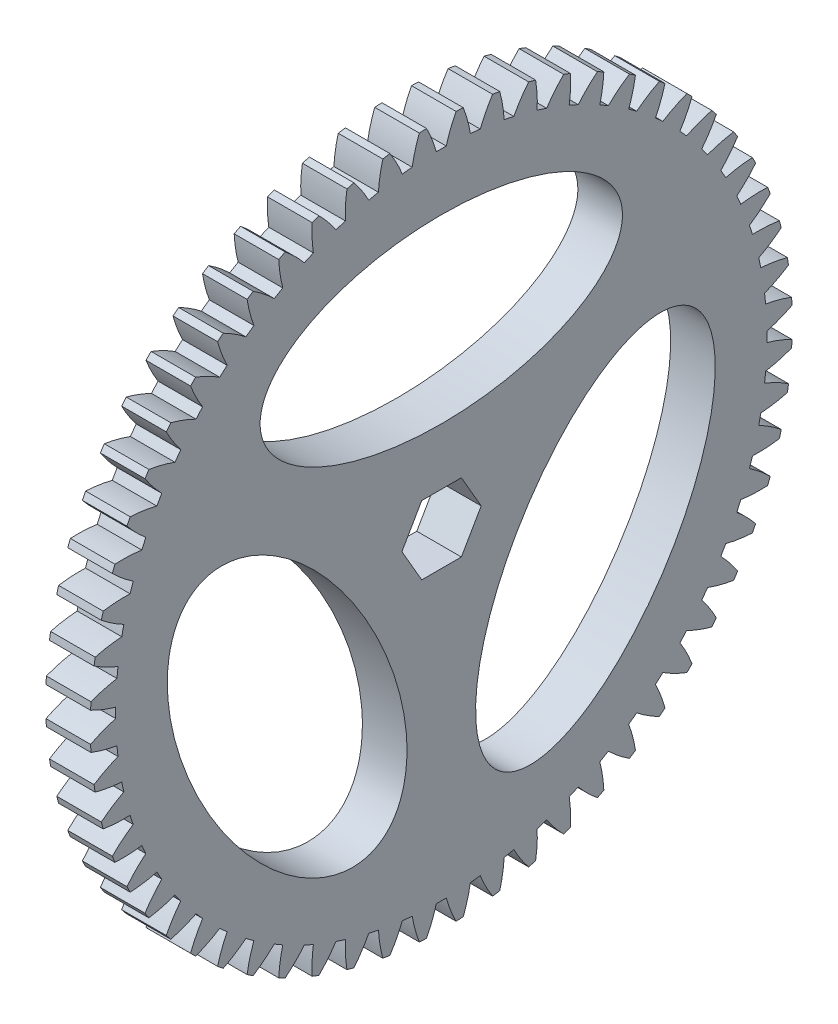
SolidWorks part; units mm, degrees
ref_plane "Plane1" through (0, 0, 0) normal (0, 0, 1) x (1, 0, 0)
ref_plane "Plane2" through (0, 0, 0) normal (0, 1, 0) x (1, 0, 0)
ref_plane "Plane3" through (0, 0, 0) normal (1, 0, 0) x (0, 0, -1)
sketch "HoldingSke" plane through (0, 0, 0) normal (0, 1, 0) x (1, 0, 0)
  line L0 (0, 0) -> (254, -439.9409)
  line L1 (-15, 0) -> (100, 0) construction
  line L2 (0, 0) -> (-2.1039, 2.3779)
  line L3 (0, 0) -> (-11.863, 4.5341)
  line L4 (0, 0) -> (4.318, 7.479)
  line L5 (0, 0) -> (-47.5972, -17.7524)
  line L6 (0, 0) -> (-4.1448, -2.7965)
  line L7 (-2.1039, 2.3779) -> (8.8308, 51.9871)
  line L8 (-76.2, 54.61) -> (-75.184, 54.61)
  line L9 (-71.009, 38.7566) -> (-53.1078, 45.2721)
  line L10 (-76.2, 71.12) -> (104.1128, 71.12)
  line L11 (0, 0) -> (-5, 0)
  line L12 (-76.2, 101.6) -> (-76.1492, 101.6)
  line L13 (24.9733, 27.94) -> (52.9518, 28.4284)
  line L14 (24.9733, 27.94) -> (25.0241, 27.9398)
  line L15 (24.9733, 27.94) -> (100.4021, 29.52)
  circle A0 centre (0, 0) radius 0.3969
  circle A1 centre (0, 0) radius 36.5252
  circle A2 centre (0, 0) radius 38.1
  circle A3 centre (0, 0) radius 0.3969
  dimension "MHD" = 73.0504
  dimension "Hub_dia" = 76.2
  dimension "Bore" = 0.7937
  dimension "MBD" = 0.7937
  dimension "Num_teeth" = 60
  dimension "Pitch" = 508
  dimension "Overall_len" = 50.8
  dimension "Show_teeth" = 60
  dimension "Thickness" = 5
  dimension "OAL" = 50.8001
  dimension "T_dim" = 1.016
  dimension "Ap" = 20
  dimension "H" = 19.05
  dimension "Pitch_radius" = 180.3128
  dimension "Width" = 5
  dimension "Backlash" = 0.0508
  dimension "Addendum_fac" = 1
  dimension "Dedendum_fac" = 1.2
  dimension "Clearance_fac" = 0.2
  dimension "Dedendum_add" = 0.0508
sketch "BasProSke" plane through (0, 0, 0) normal (0, 1, 0) x (1, 0, 0)
  line L0 (-10, 0) -> (60, 0) construction
  line L1 (0, 0) -> (0, 39.37)
  line L2 (0, 0) -> (5, 0)
  line L3 (5, 0) -> (5, 39.37)
  line L4 (5, 39.37) -> (0, 39.37)
  dimension "Thickness" = 5
  dimension "Diameter" = 78.74
revolve "Base-Revolve" add sketch "BasProSke" angle 360 about L0
sketch "TooCutSke" plane through (0, 0, 0) normal (1, 0, 0) x (0, 0, -1)
  line L1 (0, 0) -> (0, 107) construction
  line L2 (0, 0) -> (-1.0862, 38.0845) construction
  line L3 (0, 0) -> (-3.9869, 76.0739) construction
  line L4 (-1.0862, 38.0845) -> (-1.9934, 38.037) construction
  arc A0 (0.5545, 36.521) -> (-0.5545, 36.521) centre (0, 0) ccw
  arc A1 (1.6683, 39.3601) -> (-1.6683, 39.3601) centre (0, 0) ccw
  circle A2 centre (0, 0) radius 38.1 construction
  circle A3 centre (0, 0) radius 35.8023 construction
  arc A4 (-0.5545, 36.521) -> (-1.6683, 39.3601) centre (-15.2274, 32.4026) ccw
  arc A5 (1.6683, 39.3601) -> (0.5545, 36.521) centre (15.2274, 32.4026) ccw
  dimension "Root_dia" = 73.0504
  dimension "Overcut_dia" = 78.7908
  dimension "Pitch_dia" = 76.2
  dimension "Base_dia" = 71.6046
  dimension "Flank_rad" = 15.24
  dimension "Half_ang" = 3
  dimension "Half_CT" = 0.9084
extrude "ToothCut" cut sketch "TooCutSke" along normal through all
fillet "Breaks" [suppressed] radius 0.0254
fillet "RootFillets" [suppressed] radius 0.3048
pattern_circular "TeethCuts" count 60 every 6 about axis through (-10, 0, 0) along (1, 0, 0) of "ToothCut", "RootFillets", "Breaks"
sketch "HubNeaOneSke" plane through (0, 0, 0) normal (-1, 0, 0) x (0, 0, 1)
  circle A0 centre (0, 0) radius 36.5252
  dimension "Diameter" = 73.0504
extrude "HubNearOne" [suppressed] add sketch "HubNeaOneSke" along normal blind 45.8001
sketch "HubNeaBotSke" plane through (0, 0, 0) normal (-1, 0, 0) x (0, 0, 1)
  circle A0 centre (0, 0) radius 36.5252
  dimension "Diameter" = 73.0504
extrude "HubNearBoth" [suppressed] add sketch "HubNeaBotSke" along normal blind 22.9
ref_plane "FarPln" through (5, 0, 0) normal (1, 0, 0) x (0, 0, -1)
sketch "HubFarSke" plane through (5, 0, 0) normal (1, 0, 0) x (0, 0, -1)
  circle A0 centre (0, 0) radius 36.5252
  dimension "Diameter" = 73.0504
extrude "HubFar" [suppressed] add sketch "HubFarSke" along normal blind 22.9
sketch "BorSke" plane through (0, 0, 0) normal (1, 0, 0) x (0, 0, -1)
  circle A0 centre (0, 0) radius 0.3969
  dimension "Diameter" = 0.7937
extrude "Bore" cut sketch "BorSke" along normal mid plane 101.6001
sketch "KeySke" plane through (0, 0, 0) normal (1, 0, 0) x (0, 0, -1)
  line L0 (-0.127, 0) -> (-0.127, 0.6191)
  line L1 (-0.127, 0.6191) -> (0.127, 0.6191)
  line L2 (0.127, 0.6191) -> (0.127, 0)
  line L3 (0, 0) -> (0, 34) construction
  line L4 (-0.127, 0) -> (0.127, 0)
  dimension "Offset" = 0.6191
  dimension "Width" = 0.254
extrude "Keyway" [suppressed] cut sketch "KeySke" along normal mid plane 101.6001
pattern_circular "Keyway2" [suppressed] count 2 every 90 about axis through (-10, 0, 0) along (1, 0, 0)
sketch "Sketch1" plane through (5, 0, 0) normal (1, 0, 0) x (0, 0, -1)
  line L1 (2.2518, 3.4537) -> (-2.1932, 3.4537)
  line L2 (-2.1932, 3.4537) -> (-4.4157, -0.3958)
  line L3 (-4.4157, -0.3958) -> (-2.1932, -4.2453)
  line L4 (-2.1932, -4.2453) -> (2.2518, -4.2453)
  line L5 (2.2518, -4.2453) -> (4.4743, -0.3958)
  line L6 (4.4743, -0.3958) -> (2.2518, 3.4537)
  circle A0 centre (0.0293, -0.3958) radius 3.8495 construction
  circle A1 centre (0, 0) radius 0.3969 construction
  dimension "D1" = 8.89
extrude "Cut-Extrude1" cut sketch "Sketch1" against normal through all
sketch "Sketch2" plane through (5, 0, 0) normal (1, 0, 0) x (0, 0, -1)
  line L0 (2.2518, 3.4537) -> (-2.1932, 3.4537) construction
  ellipse E0 centre (0, 19.9637) end of major axis (20.32, 19.9637) minor radius 10.16
  dimension "D1" = 6.35
  dimension "D2" = 20.32
  dimension "D3" = 40.64
extrude "Cut-Extrude2" cut sketch "Sketch2" against normal through all
pattern_circular "CirPattern1" count 3 over 360 about axis through (5, 0, 0) along (-1, 0, 0) of "Cut-Extrude2"
equation "' \"Pitch@HoldingSke\" = 4"
equation "' \"Num_teeth@HoldingSke\" = 12"
equation "' \"Ap@HoldingSke\" =  20"
equation "' \"Ap@HoldingSke\" = 20"
equation "' \"Width@HoldingSke\" = 0.5"
equation "' \"Hub_dia@HoldingSke\"= 1"
equation "' \"Hub_dia@HoldingSke\" = 1"
equation "' \"Overall_len@HoldingSke\" = 1.0"
equation "' \"Bore@HoldingSke\" = 0.75"
equation "' \"T_dim@HoldingSke\" = 0.85"
equation "' \"Width@KeySke\" = 0.25"
equation "' \"Show_teeth@HoldingSke\" = 13"
equation "' \"Backlash@HoldingSke\" = 0.009"
equation "' \"Addendum_fac@HoldingSke\" = 1.0"
equation "' \"Dedendum_fac@HoldingSke\" = 1.25"
equation "' \"Dedendum_add@HoldingSke\" = 0.00005"
equation "' \"Clearance_fac@HoldingSke\" = 0.25"
equation "' \"Pitch@HoldingSke\" = 0.5"
equation "' \"Num_teeth@HoldingSke\" = 23"
equation "' \"Show_teeth@HoldingSke\" = 23"
equation "' \"Backlash@HoldingSke\" = 0.0375"
equation "\"Overcut_dia@TooCutSke\" = (\"Num_teeth@HoldingSke\" + 2 * \"Addendum_fac@HoldingSke\") / \"Pitch@HoldingSke\" + 0.002"
equation "\"Pitch_dia@TooCutSke\" = \"Num_teeth@HoldingSke\" / \"Pitch@HoldingSke\""
equation "\"Base_dia@TooCutSke\" = \"Num_teeth@HoldingSke\" / \"Pitch@HoldingSke\" * cos((\"Ap@HoldingSke\"  * 3.14159265 / 180))"
equation "\"Root_dia@TooCutSke\" = (\"Num_teeth@HoldingSke\" + 2) / \"Pitch@HoldingSke\" - 2 * (\"Addendum_fac@HoldingSke\" + \"Dedendum_fac@HoldingSke\") / \"Pitch@HoldingSke\" - \"Dedendum_add@HoldingSke\" * 2"
equation "\"Half_ang@TooCutSke\" = 180 / \"Num_teeth@HoldingSke\""
equation "\"Half_CT@TooCutSke\" = \"Num_teeth@HoldingSke\" / \"Pitch@HoldingSke\" * sin((3.14159265 / 2 / \"Num_teeth@HoldingSke\")) / 2 - 7 * \"Backlash@HoldingSke\" / 4"
equation "\"Flank_rad@TooCutSke\" = \"Num_teeth@HoldingSke\" / \"Pitch@HoldingSke\" / 5"
equation "\"Radius@RootFillets\" = \"Clearance_fac@HoldingSke\" / \"Pitch@HoldingSke\" + \"Dedendum_add@HoldingSke\""
equation "\"Break_rad@Breaks\" = 0.02 / \"Pitch@HoldingSke\""
equation "\"Thickness@HoldingSke\" = \"Width@HoldingSke\""
equation "\"OAL@HoldingSke\" = \"Thickness@HoldingSke\""
equation "\"MHD@HoldingSke\" = (\"Num_teeth@HoldingSke\" + 2) / \"Pitch@HoldingSke\" - 2 * (\"Addendum_fac@HoldingSke\" + \"Dedendum_fac@HoldingSke\")  / \"Pitch@HoldingSke\" - \"Dedendum_add@HoldingSke\" * 2"
equation "\"MBD@HoldingSke\" = (\"Num_teeth@HoldingSke\" + 2) / \"Pitch@HoldingSke\" - 2 * (\"Addendum_fac@HoldingSke\" + \"Dedendum_fac@HoldingSke\")  / \"Pitch@HoldingSke\" - \"Dedendum_add@HoldingSke\" * 2 - 0.002"
equation "\"MHD@HoldingSke\" = ((sgn( \"MHD@HoldingSke\" - \"Hub_dia@HoldingSke\" )-1)*( \"MHD@HoldingSke\" - \"Hub_dia@HoldingSke\" ))/-2+ \"Hub_dia@HoldingSke\""
equation "\"MBD@HoldingSke\" = ((sgn( \"MBD@HoldingSke\" - \"Bore@HoldingSke\" )-1)*( \"MBD@HoldingSke\" - \"Bore@HoldingSke\" ))/-2+ \"Bore@HoldingSke\""
equation "\"OAL@HoldingSke\" = ((sgn( \"OAL@HoldingSke\" - \"Overall_len@HoldingSke\" )+1)*( \"OAL@HoldingSke\" - \"Overall_len@HoldingSke\" ))/2 + \"Overall_len@HoldingSke\" + 0.000002"
equation "\"Num_teeth@TeethCuts\" = int( \"Show_teeth@HoldingSke\" ) + 1"
equation "\"Num_teeth@TeethCuts\" = ((sgn( \"Num_teeth@TeethCuts\" - \"Num_teeth@HoldingSke\" )-1)*( \"Num_teeth@TeethCuts\" - \"Num_teeth@HoldingSke\" ))/-2+ \"Num_teeth@HoldingSke\""
equation "\"Num_teeth@TeethCuts\" = ((sgn( \"Num_teeth@TeethCuts\" - 2.0)+1)*( \"Num_teeth@TeethCuts\" - 2.0))/2 +2.0"
equation "\"Angle@TeethCuts\" = 360.0 / \"Num_teeth@HoldingSke\""
equation "\"Diameter@BasProSke\" = (\"Num_teeth@HoldingSke\" + 2 * \"Addendum_fac@HoldingSke\") / \"Pitch@HoldingSke\""
equation "\"Thickness@BasProSke\"  = \"Thickness@HoldingSke\""
equation "' \"Fillet_rad@BasProSke\" =  \"Thickness@HoldingSke\" * 0.05"
equation "' \"Fillet_rad@BasProSke\" = \"Thickness@HoldingSke\" * 0.05"
equation "\"MHD@HoldingSke\" = ((sgn( \"MHD@HoldingSke\" - \"Root_dia@TooCutSke\" )-1)*( \"MHD@HoldingSke\" - \"Root_dia@TooCutSke\" ))/-2+ \"Root_dia@TooCutSke\""
equation "\"Diameter@HubNeaOneSke\" = \"MHD@HoldingSke\""
equation "\"Length@HubNearOne\" = \"OAL@HoldingSke\" - \"Thickness@BasProSke\""
equation "\"Diameter@HubNeaBotSke\" = \"MHD@HoldingSke\""
equation "\"Length@HubNearBoth\" = ( \"OAL@HoldingSke\" - \"Thickness@BasProSke\" ) / 2.0"
equation "\"Thickness@FarPln\" = \"Thickness@BasProSke\""
equation "\"Diameter@HubFarSke\" = \"MHD@HoldingSke\""
equation "\"Length@HubFar\" = ( \"OAL@HoldingSke\" - \"Thickness@BasProSke\" ) / 2.0"
equation "\"Diameter@BorSke\" = \"MBD@HoldingSke\""
equation "\"D1@Bore\" = \"OAL@HoldingSke\" * 2.0"
equation "\"D1@Keyway\" = \"OAL@HoldingSke\" * 2.0"
equation "\"Offset@KeySke\" = \"T_dim@HoldingSke\" - \"MBD@HoldingSke\" / 2.0"
